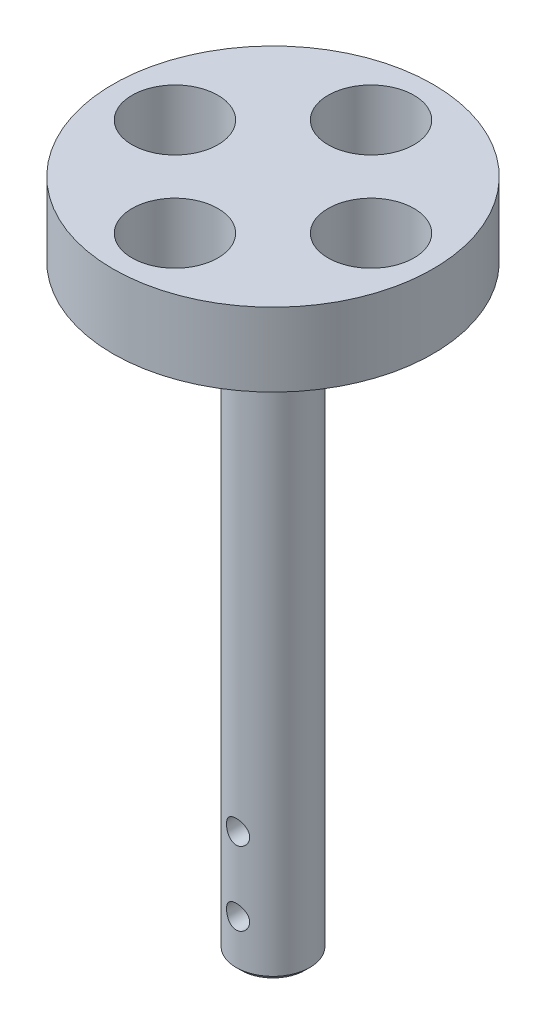
SolidWorks part; units mm, degrees
ref_plane "前视基准面" through (0, 0, 0) normal (0, 0, 1) x (1, 0, 0)
ref_plane "上视基准面" through (0, 0, 0) normal (0, 1, 0) x (1, 0, 0)
ref_plane "右视基准面" through (0, 0, 0) normal (1, 0, 0) x (0, 0, -1)
sketch "Sketch1" plane through (0, 0, 0) normal (0, 1, 0) x (1, 0, 0)
  circle A0 centre (0, 0) radius 20.7264
  dimension "D1" = 41.4528
extrude "Boss-Extrude1" add sketch "Sketch1" along normal blind 9.525
sketch "Sketch2" plane through (0, 9.525, 0) normal (0, 1, 0) x (1, 0, 0)
  circle A0 centre (0, 12.7) radius 5.5626
  dimension "D1" = 11.1252
  dimension "D2" = 12.7
extrude "Cut-Extrude1" cut sketch "Sketch2" against normal blind 7.9375
pattern_circular "CirPattern1" count 4 over 360 about axis through (0, 0, 0) along (0, 1, 0) of "Cut-Extrude1"
sketch "Sketch3" plane through (0, 0, 0) normal (0, -1, 0) x (1, 0, 0)
  circle A0 centre (0, 0) radius 4.7625
  dimension "D1" = 9.525
extrude "Boss-Extrude2" add sketch "Sketch3" along normal blind 77.47
sketch "Sketch4" plane through (0, 0, 0) normal (0, 0, 1) x (1, 0, 0)
  line L0 (-20.7264, 0) -> (-4.7625, -6.35)
  line L1 (-4.7625, 0) -> (-4.7625, -77.47) construction
  line L2 (-4.7625, -6.35) -> (-4.7625, 0)
  line L3 (-20.7264, 0) -> (20.7264, 0) construction
  line L4 (-4.7625, 0) -> (-20.7264, 0)
  line L5 (0, 0) -> (0, -13.8998) construction
  dimension "D1" = 6.35
revolve "Revolve1" add sketch "Sketch4" angle 360 about L5
sketch "Sketch5" plane through (0, 0, 0) normal (0, 0, 1) x (1, 0, 0)
  line L0 (-4.7625, -77.47) -> (4.7625, -77.47) construction
  circle A0 centre (0, -71.12) radius 1.5
  circle A1 centre (0, -61.595) radius 1.5
  dimension "D1" = 3
  dimension "D2" = 3
  dimension "D3" = 9.525
  dimension "D4" = 6.35
extrude "Cut-Extrude2" cut sketch "Sketch5" against normal through all and the other way through all
sketch "Sketch6" plane through (0, 1.5875, 0) normal (0, 1, 0) x (1, 0, 0)
  circle A0 centre (-12.7, 0) radius 3.175
  dimension "D1" = 6.35
extrude "Cut-Extrude3" cut sketch "Sketch6" against normal through all
pattern_circular "CirPattern2" count 4 over 360 about axis through (0, 0, 0) along (0, 1, 0) of "Cut-Extrude3"
chamfer "Chamfer1" distance 0.635 angle 45 1 edges at (0, -77.47, -4.7625)
